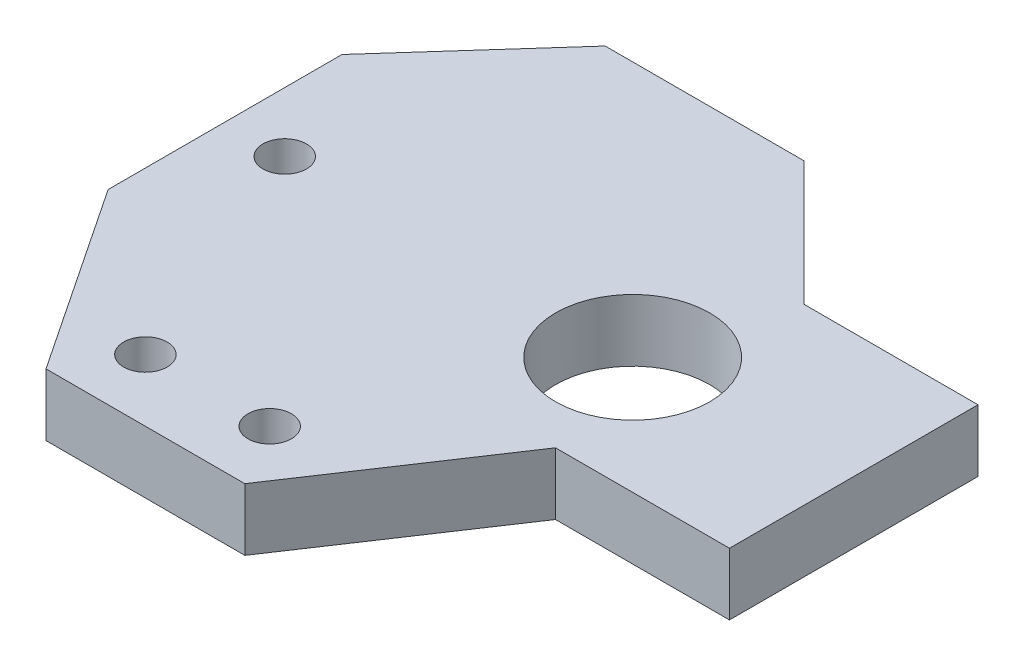
SolidWorks part; units mm, degrees
ref_plane "Front Plane" through (0, 0, 0) normal (0, 0, 1) x (1, 0, 0)
ref_plane "Top Plane" through (0, 0, 0) normal (0, 1, 0) x (1, 0, 0)
ref_plane "Right Plane" through (0, 0, 0) normal (1, 0, 0) x (0, 0, -1)
sketch "Sketch1" plane through (0, 0, 0) normal (0, 1, 0) x (1, 0, 0)
  line L0 (0, 33.8197) -> (10, 45)
  line L1 (0, 0) -> (50, 0)
  line L2 (0, 0) -> (0, 45)
  line L3 (0, 45) -> (50, 45)
  line L4 (50, 0) -> (50, 45)
  line L5 (0, 15) -> (10, 0)
  line L6 (26, 45) -> (36, 35)
  line L7 (26, 0) -> (36, 15)
  line L8 (36, 15) -> (50, 15)
  line L9 (36, 35) -> (50, 35)
  line L10 (50, 25) -> (0, 25) construction
  circle A1 centre (13, 5) radius 1.75
  circle A2 centre (23, 5) radius 1.75
  dimension "D15" = 10
  dimension "D16" = 3.5
  dimension "D24" = 3
  dimension "D25" = 3
  dimension "D17" = 3.5
  dimension "D1" = 45
  dimension "D2" = 50
  dimension "D3" = 15
  dimension "D4" = 10
  dimension "D5" = 10
  dimension "D6" = 15
  dimension "D7" = 16
  dimension "D8" = 16
  dimension "D9" = 10
  dimension "D10" = 10
  dimension "D11" = 10
  dimension "D12" = 20
  dimension "D13" = 10
  dimension "D18" = 5
extrude "Boss-Extrude1" add sketch "Sketch1" along normal blind 5
ref_plane "Plane1" through (0, 0, 0) normal (0, -1, 0) x (-1, 0, 0)
sketch "Sketch2" plane through (0, 0, 0) normal (0, -1, 0) x (-1, 0, 0)
  line L0 (0, 24.4098) -> (-68.9029, 24.4098) construction
  line L1 (0, 15) -> (0, 33.8197) construction
  circle A0 centre (-4.8, 24.4098) radius 1.75
  circle A1 centre (-32.8, 24.4098) radius 6.2
  dimension "D1" = 4.8
  dimension "D2" = 12.4
  dimension "D3" = 28
extrude "Cut-Extrude1" cut sketch "Sketch2" against normal blind 10
